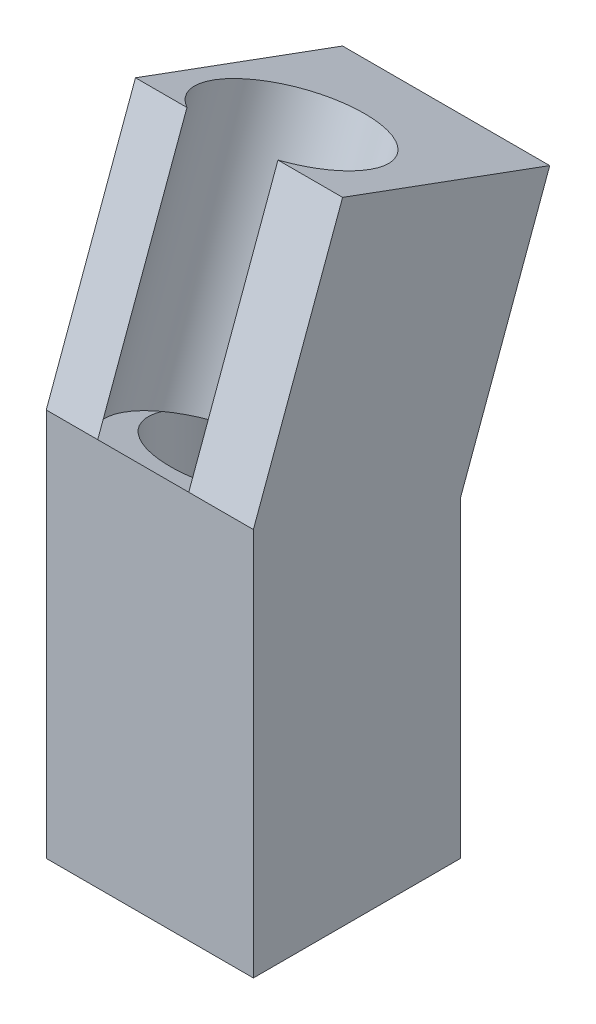
SolidWorks part; units mm, degrees
ref_plane "Front Plane" through (0, 0, 0) normal (0, 0, 1) x (1, 0, 0)
ref_plane "Top Plane" through (0, 0, 0) normal (0, 1, 0) x (1, 0, 0)
ref_plane "Right Plane" through (0, 0, 0) normal (1, 0, 0) x (0, 0, -1)
sketch "Sketch1" plane through (0, 0, 0) normal (0, 1, 0) x (1, 0, 0)
  line L1 (0, 0) -> (8, 0)
  line L2 (0, 0) -> (0, 8)
  line L3 (0, 8) -> (8, 8)
  line L4 (8, 0) -> (8, 8)
  circle A0 centre (3.9956, 3.7914) radius 3
  dimension "D1" = 8
  dimension "D2" = 8
extrude "Boss-Extrude3" add sketch "Sketch1" along normal blind 15
sketch "Sketch3" plane through (0, 0, 0) normal (-1, 0, 0) x (0, 0, 1)
  line L0 (-8, 15) -> (0, 15)
  line L1 (0, 15) -> (-8, 12.0631)
  line L2 (-8, 15) -> (-8, 0) construction
  line L3 (-8, 12.0631) -> (-8, 15)
  point P4 (-8, 12.5988)
  point P8 (-8, 12.0631)
extrude "Cut-Extrude1" cut sketch "Sketch3" against normal blind 8
sketch "Sketch4" plane through (0, 13.2185, -4.8527) normal (0, 0.9387, -0.3446) x (1, 0, 0)
  line L1 (0, 3.3527) -> (8, 3.3527)
  line L2 (0, 3.3527) -> (0, -5.1693)
  line L3 (0, -5.1693) -> (8, -5.1693)
  line L4 (8, 3.3527) -> (8, -5.1693)
extrude "Boss-Extrude4" add sketch "Sketch4" along normal blind 10
sketch "Sketch5" plane through (0, 22.6059, -8.2989) normal (0, 0.9387, -0.3446) x (1, 0, 0)
  circle A0 centre (3.7455, -2.738) radius 3
extrude "Cut-Extrude2" cut sketch "Sketch5" against normal blind 10
